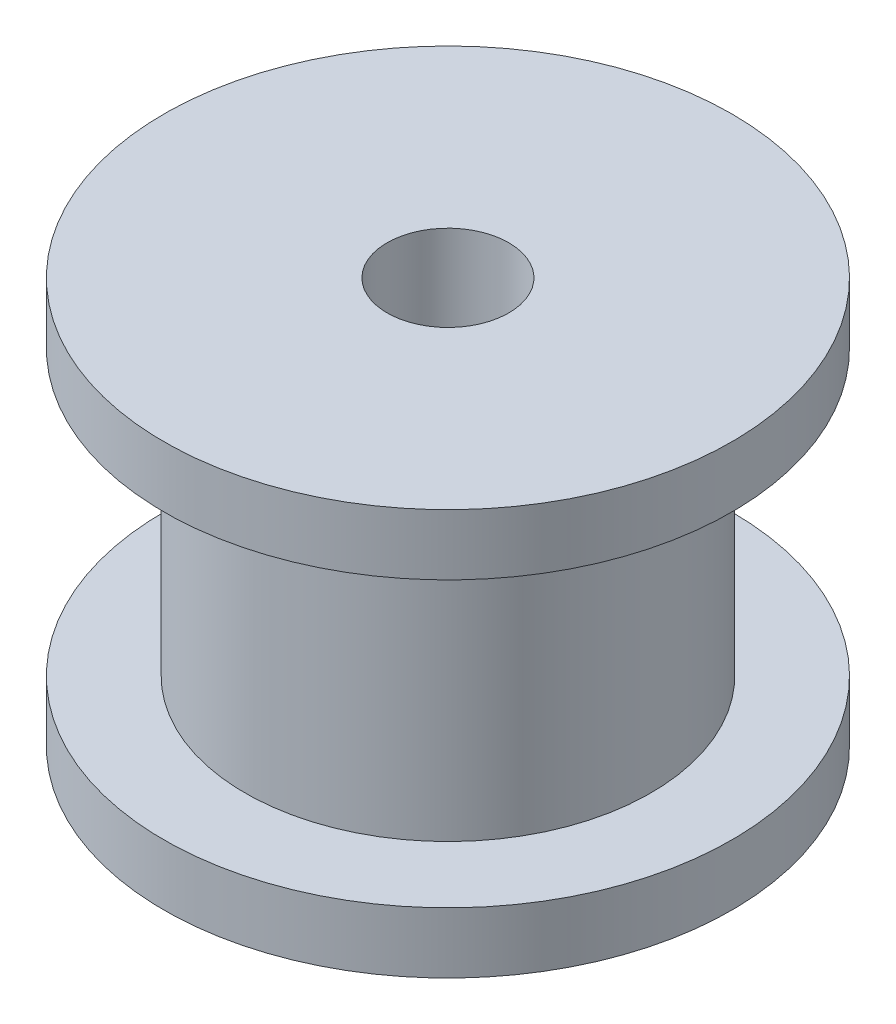
SolidWorks part; units mm, degrees
ref_plane "前视基准面" through (0, 0, 0) normal (0, 0, 1) x (1, 0, 0)
ref_plane "上视基准面" through (0, 0, 0) normal (0, 1, 0) x (1, 0, 0)
ref_plane "右视基准面" through (0, 0, 0) normal (1, 0, 0) x (0, 0, -1)
sketch "Sketch1" plane through (0, 0, 0) normal (0, 0, 1) x (1, 0, 0)
  line L0 (1.5, 0) -> (7, 0)
  line L1 (7, 0) -> (7, 1.5)
  line L2 (7, 1.5) -> (5, 1.5)
  line L3 (5, 1.5) -> (5, 8.5)
  line L4 (5, 8.5) -> (7, 8.5)
  line L5 (7, 8.5) -> (7, 10)
  line L7 (0, 0) -> (0, 10) construction
  line L8 (0, 10) -> (1.5, 10) construction
  line L9 (1.5, 10) -> (1.5, 0)
  line L10 (1.5, 10) -> (7, 10)
  dimension "D1" = 10
  dimension "D2" = 7
  dimension "D3" = 1.5
  dimension "D4" = 5
  dimension "D5" = 7
  dimension "D6" = 1.5
  dimension "D7" = 7
revolve "Revolve1" add sketch "Sketch1" angle 360 about L7
ref_plane "Plane1" through (0, 5, 0) normal (0, -1, 0) x (-1, 0, 0)
sketch "Sketch2" plane through (0, 5, 0) normal (0, -1, 0) x (-1, 0, 0)
  circle A0 centre (0, 0) radius 5 construction
  dimension "D1" = 10
